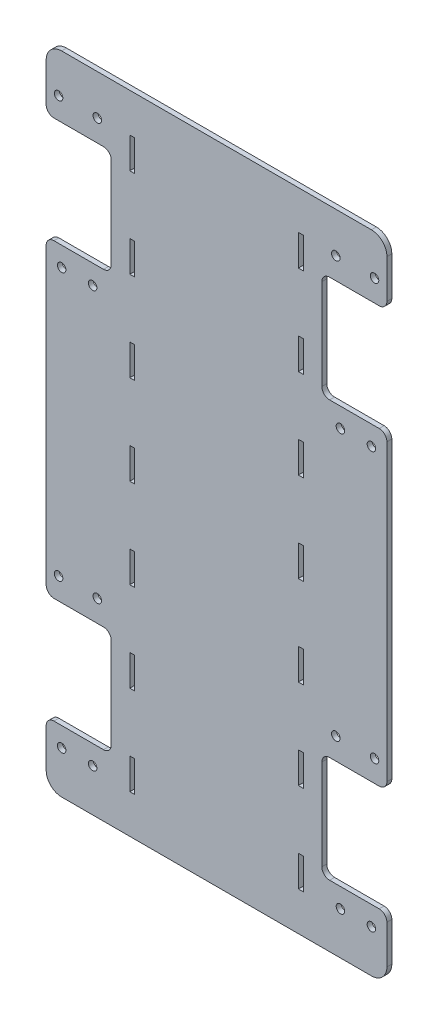
SolidWorks part; units mm, degrees
ref_plane "Plan de face" through (0, 0, 0) normal (0, 0, 1) x (1, 0, 0)
ref_plane "Plan de dessus" through (0, 0, 0) normal (0, 1, 0) x (1, 0, 0)
ref_plane "Plan de droite" through (0, 0, 0) normal (1, 0, 0) x (0, 0, -1)
sketch "Esquisse1" plane through (0, 0, 0) normal (0, 0, 1) x (1, 0, 0)
  line L0 (110, 208.6) -> (-110, 208.6)
  line L1 (-110, 208.6) -> (-110, 168.6)
  line L2 (-110, 168.6) -> (-68, 168.6)
  line L3 (-68, 168.6) -> (-68, 100)
  line L4 (-68, 100) -> (-110, 100)
  line L5 (-110, 100) -> (-110, -100)
  line L6 (-110, -100) -> (-68, -100)
  line L7 (-68, -100) -> (-68, -168.6)
  line L8 (-68, -168.6) -> (-110, -168.6)
  line L9 (-110, -168.6) -> (-110, -208.6)
  line L10 (-110, -208.6) -> (110, -208.6)
  line L11 (110, -208.6) -> (110, -168.6)
  line L12 (110, -168.6) -> (68, -168.6)
  line L13 (68, -168.6) -> (68, -100)
  line L14 (68, -100) -> (110, -100)
  line L15 (110, -100) -> (110, 100)
  line L16 (110, 100) -> (68, 100)
  line L17 (68, 100) -> (68, 168.6)
  line L18 (68, 168.6) -> (110, 168.6)
  line L19 (110, 168.6) -> (110, 208.6)
  point P17 (0, 208.6)
  point P22 (-110, 0)
  point P24 (-110, 188.6)
  dimension "D1" = 68.6
  dimension "D2" = 42
  dimension "D3" = 42
  dimension "D4" = 220
  dimension "D5" = 200
  dimension "D6" = 68.6
  dimension "D8" = 40
  dimension "D7" = 40
  dimension "D9" = 417.2
extrude "Boss.-Extru.1" add sketch "Esquisse1" along normal blind 3.175
sketch "Esquisse2" plane through (0, 0, 3.175) normal (0, 0, 1) x (1, 0, 0)
  line L0 (110, 208.6) -> (-110, 208.6) construction
  line L1 (-56, 183.6) -> (-52.825, 183.6)
  line L2 (-56, 183.6) -> (-56, 163.6)
  line L3 (-56, 163.6) -> (-52.825, 163.6)
  line L4 (-52.825, 183.6) -> (-52.825, 163.6)
  line L9 (-68, 168.6) -> (-68, 100) construction
  line L44 (-56, 125.7333) -> (-56, 105.7333)
  line L45 (-56, 125.7333) -> (-52.825, 125.7333)
  line L46 (-52.825, 125.7333) -> (-52.825, 105.7333)
  line L47 (-56, 105.7333) -> (-52.825, 105.7333)
  line L48 (-56, 67.8667) -> (-56, 47.8667)
  line L49 (-56, 67.8667) -> (-52.825, 67.8667)
  line L50 (-52.825, 67.8667) -> (-52.825, 47.8667)
  line L51 (-56, 47.8667) -> (-52.825, 47.8667)
  line L52 (-56, 10) -> (-56, -10)
  line L53 (-56, 10) -> (-52.825, 10)
  line L54 (-52.825, 10) -> (-52.825, -10)
  line L55 (-56, -10) -> (-52.825, -10)
  line L56 (-56, -47.8667) -> (-56, -67.8667)
  line L57 (-56, -47.8667) -> (-52.825, -47.8667)
  line L58 (-52.825, -47.8667) -> (-52.825, -67.8667)
  line L59 (-56, -67.8667) -> (-52.825, -67.8667)
  line L60 (-56, -105.7333) -> (-56, -125.7333)
  line L61 (-56, -105.7333) -> (-52.825, -105.7333)
  line L62 (-52.825, -105.7333) -> (-52.825, -125.7333)
  line L63 (-56, -125.7333) -> (-52.825, -125.7333)
  line L64 (-56, -163.6) -> (-56, -183.6)
  line L65 (-56, -163.6) -> (-52.825, -163.6)
  line L66 (-52.825, -163.6) -> (-52.825, -183.6)
  line L67 (-56, -183.6) -> (-52.825, -183.6)
  line L69 (-110, -208.6) -> (110, -208.6) construction
  dimension "D1" = 25
  dimension "D2" = 12
  dimension "D3" = 20
  dimension "D6" = 25
  dimension "D4" = 3.175
  dimension "D5" = 7
extrude "Enlèv. mat.-Extru.1" cut sketch "Esquisse2" against normal through all both and the other way through all
mirror "Symétrie1" about plane through (0, 0, 0) normal (1, 0, 0) of "Enlèv. mat.-Extru.1"
hole_wizard "Dégagement M51" positions "Esquisse3D1" profile "Esquisse4" hole size "M5" standard "Ansi Metric" end condition through all
sketch3d "Esquisse3D1"
  line L0 (-110, 168.6, 3.175) -> (-68, 168.6, 3.175) construction
  line L5 (-110, -100, 3.175) -> (-68, -100, 3.175) construction
  line L6 (-110, 208.6, 3.175) -> (-110, 168.6, 3.175) construction
  line L7 (110, 168.6, 3.175) -> (110, 208.6, 3.175) construction
  line L8 (-68, 100, 3.175) -> (-110, 100, 3.175) construction
  line L9 (-110, 100, 3.175) -> (-110, -100, 3.175) construction
  line L10 (110, -100, 3.175) -> (110, 100, 3.175) construction
  line L11 (-68, -168.6, 3.175) -> (-110, -168.6, 3.175) construction
  point P0 (100, -181.1, 3.175)
  point P2 (80, -181.1, 3.175)
  point P4 (-100, -181.1, 3.175)
  point P6 (-80, -181.1, 3.175)
  point P8 (-102, -86, 3.175)
  point P10 (-77, -86, 3.175)
  point P12 (77, -86, 3.175)
  point P14 (102, -86, 3.175)
  point P16 (80, 87.5, 3.175)
  point P22 (100, 87.5, 3.175)
  point P26 (77, 182.6, 3.175)
  point P28 (102, 182.6, 3.175)
  point P30 (-100, 87.5, 3.175)
  point P32 (-80, 87.5, 3.175)
  point P34 (-102, 182.6, 3.175)
  point P36 (-77, 182.6, 3.175)
  dimension "D4" = 25
  dimension "D1" = 14
  dimension "D2" = 25
  dimension "D5" = 14
  dimension "D3" = 8
  dimension "D6" = 8
  dimension "D7" = 12.5
  dimension "D8" = 20
  dimension "D9" = 10
  dimension "D10" = 10
  dimension "D11" = 20
  dimension "D12" = 12.5
sketch "Esquisse4" plane through (100, -181.1, 3.175) normal (1, 0, 0) x (0, -1, 0)
  line L0 (0, 0) -> (0, 3.175)
  line L1 (0, 3.175) -> (2.75, 3.175)
  line L2 (2.75, 3.175) -> (2.75, 0)
  line L5 (2.75, 0) -> (0, 0)
  line L11 (0, -6.35) -> (0, 107.95) construction
  dimension "Diamètre du perçage jusqu'au prochain" = 5.5
  dimension "Profondeur du perçage jusqu'au prochain" = 3.175
fillet "Congé1" radius 5 16 edges at (-110, 168.6, 1.5875) (110, 168.6, 1.5875) (110, 100, 1.5875) (68, 100, 1.5875) (68, 168.6, 1.5875) (68, -100, 1.5875) (110, -168.6, 1.5875) (110, -100, 1.5875) (68, -168.6, 1.5875) (-68, 100, 1.5875) (-68, 168.6, 1.5875) (-68, -100, 1.5875) (-68, -168.6, 1.5875) (-110, -168.6, 1.5875) (-110, -100, 1.5875) (-110, 100, 1.5875)
fillet "Congé2" radius 10 4 edges at (110, -208.6, 1.5875) (-110, -208.6, 1.5875) (-110, 208.6, 1.5875) (110, 208.6, 1.5875)
sketch "Sketch1" plane through (0, 0, 0) normal (0, 0, -1) x (-1, 0, 0)
  line L0 (-25.5, 158.6) -> (-25.5, -212.4689) construction
  line L1 (-68, 105) -> (-68, 163.6) construction
  line L2 (-100, 208.6) -> (100, 208.6) construction
  text T0 "QuadrUS" font "Century Gothic" height in points 200
  dimension "D1" = 42.5
  dimension "D2" = 50
extrude "Cut-Extrude3" cut sketch "Sketch1" against normal blind 1
equation "\"D3@Esquisse1\"=\"D2@Esquisse1\""
equation "\"D6@Esquisse1\"=\"D1@Esquisse1\""
equation "\"D6@Esquisse2\"=\"D1@Esquisse2\""
equation "\"EpaisseurBois\"= 3.175mm"
equation "\"D4@Esquisse3D1\"=\"D2@Esquisse3D1\""
equation "\"D5@Esquisse3D1\"=\"D1@Esquisse3D1\""
equation "\"D6@Esquisse3D1\"=\"D3@Esquisse3D1\""
equation "\"D10@Esquisse3D1\"=\"D9@Esquisse3D1\""
equation "\"D11@Esquisse3D1\"=\"D8@Esquisse3D1\""
equation "\"D12@Esquisse3D1\"=\"D7@Esquisse3D1\""
